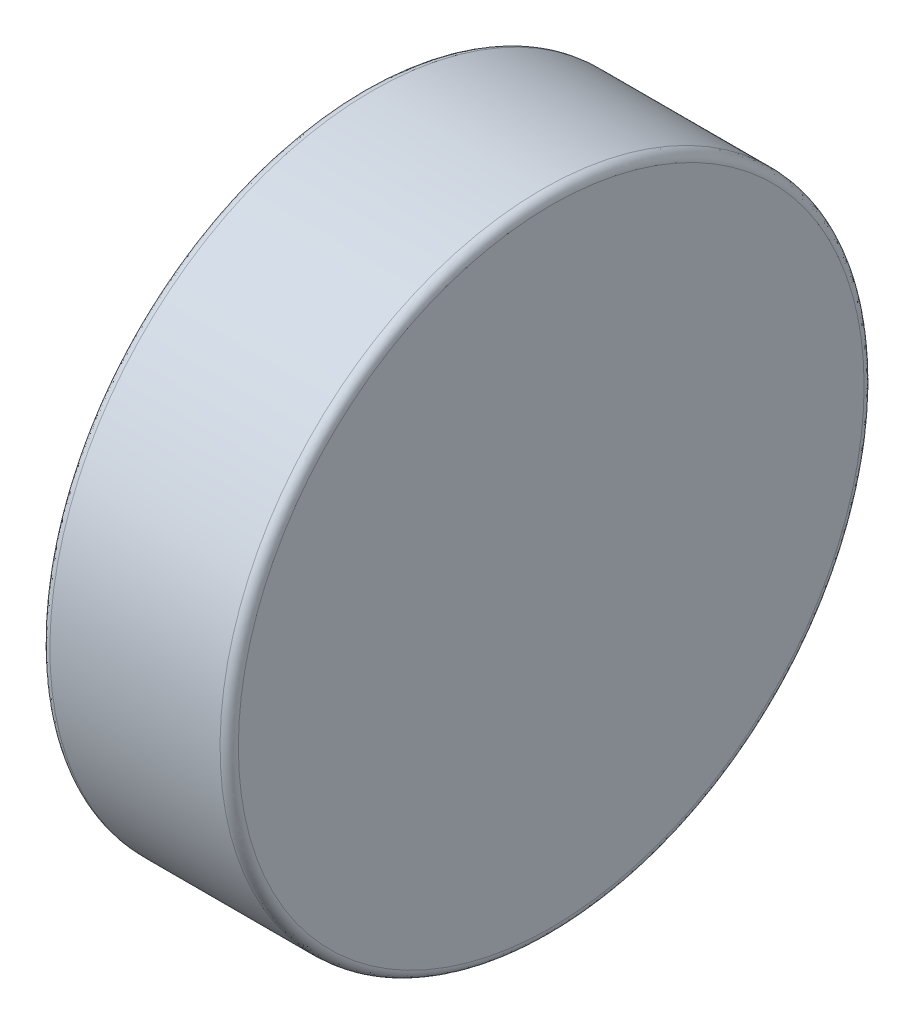
SolidWorks part; units mm, degrees
ref_plane "Front Plane" through (0, 0, 0) normal (0, 0, 1) x (1, 0, 0)
ref_plane "Top Plane" through (0, 0, 0) normal (0, 1, 0) x (1, 0, 0)
ref_plane "Right Plane" through (0, 0, 0) normal (1, 0, 0) x (0, 0, -1)
sketch "Sketch1" plane through (0, 0, 0) normal (0, 0, 1) x (1, 0, 0)
  line L0 (-10.3, 34.2) -> (-10.3, 0)
  line L1 (-10.3, 0) -> (10.3, 0)
  line L2 (10.3, 0) -> (10.3, 34.2)
  line L3 (9.3, 35.2) -> (-9.3, 35.2)
  spline S0 degree 8 poles (9.3, 35.2) (9.4964, 35.2001) (9.6928, 35.1561) (9.8777, 35.068) (10.0395, 34.9395) (10.168, 34.7777) (10.2561, 34.5928) (10.3001, 34.3964) (10.3, 34.2) knots 0 0 0 0 0 0 0 0 0 1.571973 1.571973 1.571973 1.571973 1.571973 1.571973 1.571973 1.571973 1.571973
  spline S1 degree 8 poles (-10.3, 34.2) (-10.3001, 34.3964) (-10.2561, 34.5928) (-10.168, 34.7777) (-10.0395, 34.9395) (-9.8777, 35.068) (-9.6928, 35.1561) (-9.4964, 35.2001) (-9.3, 35.2) knots -1.571973 -1.571973 -1.571973 -1.571973 -1.571973 -1.571973 -1.571973 -1.571973 -1.571973 0 0 0 0 0 0 0 0 0
  point P5 (0, 0)
  point P7 (0, 35.2)
  dimension "D1" = 35.2
  dimension "D2" = 20.6
  dimension "D3" = 34.2
  dimension "D4" = 34.2
  dimension "D5" = 18.6
revolve "Revolve1" add sketch "Sketch1" angle 360 about L1
equation "\"D4@Sketch1\"=\"D3@Sketch1\""
